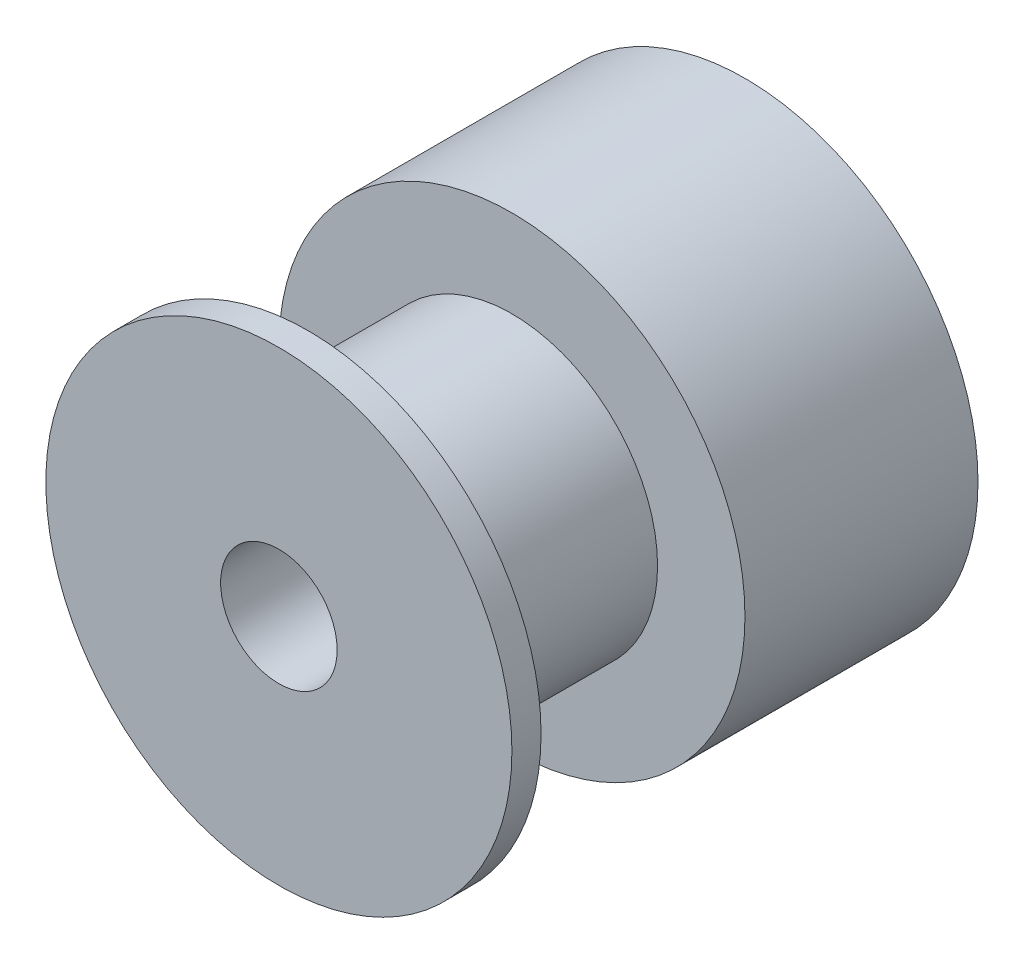
SolidWorks part; units mm, degrees
ref_plane "前视基准面" through (0, 0, 0) normal (0, 0, 1) x (1, 0, 0)
ref_plane "上视基准面" through (0, 0, 0) normal (0, 1, 0) x (1, 0, 0)
ref_plane "右视基准面" through (0, 0, 0) normal (1, 0, 0) x (0, 0, -1)
other "Configuration Table"
sketch "草图1" plane through (0, 0, 0) normal (0, 0, 1) x (1, 0, 0)
  circle A0 centre (0, 0) radius 8
  circle A1 centre (0, 0) radius 2
  dimension "D1" = 16
  dimension "D2" = 4
extrude "凸台-拉伸1" add sketch "草图1" along normal blind 8
sketch "草图3" plane through (0, 0, 8) normal (0, 0, 1) x (1, 0, 0)
  circle A0 centre (0, 0) radius 2
  circle A1 centre (0, 0) radius 5
  dimension "D1" = 10
extrude "凸台-拉伸2" add sketch "草图3" along normal blind 7
sketch "草图4" plane through (0, 0, 15) normal (0, 0, 1) x (1, 0, 0)
  circle A0 centre (0, 0) radius 2
  circle A1 centre (0, 0) radius 8
extrude "凸台-拉伸3" add sketch "草图4" along normal blind 1
